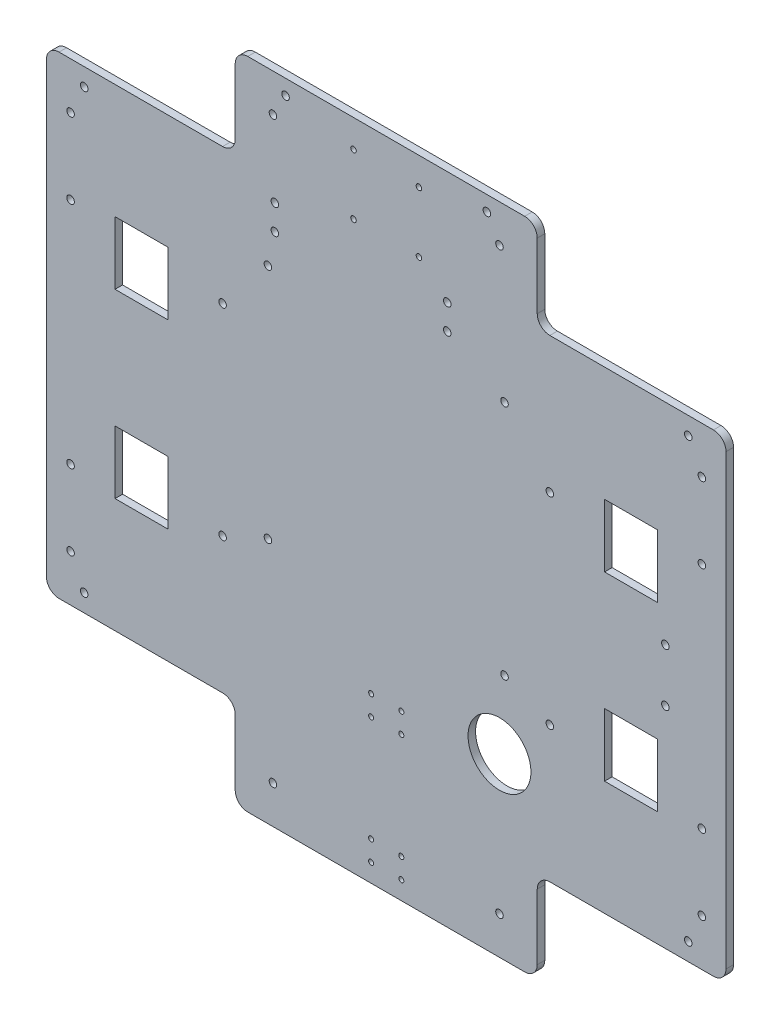
SolidWorks part; units mm, degrees
ref_plane "前视基准面" through (0, 0, 0) normal (0, 0, 1) x (1, 0, 0)
ref_plane "上视基准面" through (0, 0, 0) normal (0, 1, 0) x (1, 0, 0)
ref_plane "右视基准面" through (0, 0, 0) normal (1, 0, 0) x (0, 0, -1)
other "Configuration Table"
sketch "草图1" plane through (0, 0, 0) normal (0, 0, 1) x (1, 0, 0)
  line L1 (-135, -130) -> (135, -130)
  line L2 (-135, -130) -> (-135, 130)
  line L3 (-135, 130) -> (135, 130)
  line L4 (135, -130) -> (135, 130)
  line L5 (-135, -130) -> (135, 130) construction
  line L6 (-135, 130) -> (135, -130) construction
  point P0 (0, 0)
  dimension "D1" = 270
  dimension "D2" = 260
extrude "凸台-拉伸1" add sketch "草图1" along normal blind 3
sketch "草图2" plane through (0, 0, 0) normal (0, 0, -1) x (-1, 0, 0)
  line L0 (105.75, -40) -> (105.75, -46.5) construction
  line L1 (135, -130) -> (60, -130)
  line L2 (135, -130) -> (135, -94)
  line L3 (135, -94) -> (60, -94)
  line L4 (60, -130) -> (60, -94)
  line L5 (107.75, -48.5) -> (86.75, -48.5)
  line L6 (107.75, -48.5) -> (107.75, -23.5)
  line L7 (107.75, -23.5) -> (86.75, -23.5)
  line L8 (86.75, -48.5) -> (86.75, -23.5)
  line L9 (-135, 130) -> (-60, 130)
  line L10 (89.25, -46.5) -> (105.75, -46.5) construction
  line L11 (-179.2908, 0) -> (257.8467, 0) construction
  line L12 (0, 167.905) -> (0, -190.469) construction
  line L13 (-86.75, -48.5) -> (-86.75, -23.5)
  line L14 (-107.75, -23.5) -> (-86.75, -23.5)
  line L15 (-107.75, -48.5) -> (-107.75, -23.5)
  line L16 (-107.75, -48.5) -> (-86.75, -48.5)
  line L17 (-60, -130) -> (-60, -94)
  line L18 (-135, -94) -> (-60, -94)
  line L19 (-135, -130) -> (-135, -94)
  line L20 (-135, -130) -> (-60, -130)
  line L21 (-135, 130) -> (-135, 94)
  line L22 (-135, 94) -> (-60, 94)
  line L23 (-60, 130) -> (-60, 94)
  line L24 (-107.75, 48.5) -> (-86.75, 48.5)
  line L25 (-107.75, 48.5) -> (-107.75, 23.5)
  line L26 (-107.75, 23.5) -> (-86.75, 23.5)
  line L27 (-86.75, 48.5) -> (-86.75, 23.5)
  line L28 (86.75, 48.5) -> (86.75, 23.5)
  line L29 (107.75, 23.5) -> (86.75, 23.5)
  line L30 (107.75, 48.5) -> (107.75, 23.5)
  line L31 (107.75, 48.5) -> (86.75, 48.5)
  line L32 (60, 130) -> (60, 94)
  line L33 (135, 94) -> (60, 94)
  line L34 (135, 130) -> (135, 94)
  line L35 (135, 130) -> (60, 130)
  dimension "D1" = 36
  dimension "D2" = 75
  dimension "D3" = 25
  dimension "D4" = 21
  dimension "D5" = 2
  dimension "D6" = 2
extrude "切除-拉伸1" cut sketch "草图2" against normal up to next
fillet "圆角1" radius 5 12 edges at (135, 94, 1.5) (135, -94, 1.5) (60, -94, 1.5) (60, -130, 1.5) (-60, -130, 1.5) (-60, -94, 1.5) (-135, -94, 1.5) (-135, 94, 1.5) (-60, 94, 1.5) (-60, 130, 1.5) (60, 94, 1.5) (60, 130, 1.5)
sketch "草图3" plane through (0, 0, 3) normal (0, 0, 1) x (1, 0, 0)
  line L0 (-65.1682, -45) -> (56.9292, -45) construction
  line L1 (-50, -35) -> (50, -35) construction
  circle A0 centre (-47, -32) radius 1.5
  circle A1 centre (47, -32) radius 1.5
  circle A2 centre (47, 62) radius 1.5
  circle A3 centre (-47, 62) radius 1.5
  dimension "D1" = 10
extrude "切除-拉伸2" cut sketch "草图3" against normal blind 10
sketch "草图4" plane through (0, 0, 3) normal (0, 0, 1) x (1, 0, 0)
  line L0 (55, 130) -> (-55, 130) construction
  line L1 (60, 125) -> (60, 99) construction
  line L2 (65, 94) -> (130, 94) construction
  line L3 (135, -89) -> (135, 89) construction
  line L4 (130, -94) -> (65, -94) construction
  line L5 (135, -91) -> (135, -30) construction
  line L6 (-55, -130) -> (55, -130) construction
  line L7 (60, -99) -> (60, -125) construction
  line L8 (0, 0) -> (0, -302.2248) construction
  line L10 (-65, -40) -> (65, -40) construction
  line L11 (-65, -40) -> (-65, 40) construction
  line L12 (-65, 40) -> (65, 40) construction
  line L13 (65, -40) -> (65, 40) construction
  line L14 (-65, -40) -> (65, 40) construction
  line L15 (-65, 40) -> (65, -40) construction
  circle A1 centre (45, 115) radius 1.5
  circle A2 centre (120, 87) radius 1.5
  circle A3 centre (120, -87) radius 1.5
  circle A4 centre (45, -115) radius 1.5
  circle A5 centre (-45, -115) radius 1.5
  circle A6 centre (-120, -87) radius 1.5
  circle A7 centre (-120, 87) radius 1.5
  circle A8 centre (-45, 115) radius 1.5
  circle A11 centre (-65, 40) radius 1.5
  circle A12 centre (65, 40) radius 1.5
  circle A13 centre (-65, -40) radius 1.5
  circle A14 centre (65, -40) radius 1.5
  point P35 (0, 0)
  dimension "D1" = 15
  dimension "D2" = 15
  dimension "D3" = 3
  dimension "D4" = 7
  dimension "D5" = 15
  dimension "D6" = 3
  dimension "D7" = 7
  dimension "D8" = 15
  dimension "D9" = 3
  dimension "D10" = 15
  dimension "D11" = 15
  dimension "D12" = 3
  dimension "D15" = 3
  dimension "D16" = 3
  dimension "D17" = 3
  dimension "D18" = 3
  dimension "D13" = 130
  dimension "D14" = 80
extrude "切除-拉伸3" cut sketch "草图4" against normal through all
sketch "草图5" plane through (0, 0, 3) normal (0, 0, 1) x (1, 0, 0)
  line L0 (-149.5707, 0) -> (200.701, 0) construction
  line L1 (0, 155.8586) -> (0, -194.8252) construction
  circle A0 centre (125.4084, -45.5) radius 1.5
  circle A1 centre (125.4069, -75.5) radius 1.5
  circle A2 centre (125.4069, 75.5) radius 1.5
  circle A3 centre (125.4084, 45.5) radius 1.5
  circle A4 centre (-125.4069, -75.5) radius 1.5
  circle A5 centre (-125.4084, -45.5) radius 1.5
  circle A6 centre (-125.4084, 45.5) radius 1.5
  circle A7 centre (-125.4069, 75.5) radius 1.5
  dimension "D1" = 3
  dimension "D2" = 3
extrude "切除-拉伸4" cut sketch "草图5" against normal through all
sketch "草图6" plane through (0, 0, 3) normal (0, 0, 1) x (1, 0, 0)
  circle A0 centre (-6, -114.75) radius 1
  circle A1 centre (6, -114.75) radius 1
  circle A2 centre (-6, -122.75) radius 1
  circle A3 centre (6, -122.75) radius 1
  circle A4 centre (-6, -72.75) radius 1
  circle A5 centre (6, -72.75) radius 1
  circle A6 centre (-6, -64.75) radius 1
  circle A7 centre (6, -64.75) radius 1
extrude "切除-拉伸5" cut sketch "草图6" against normal through all
sketch "草图7" plane through (0, 0, 3) normal (0, 0, 1) x (1, 0, 0)
  circle A0 centre (110.9, 10.5) radius 1.5
  circle A1 centre (110.9, -10.5) radius 1.5
extrude "切除-拉伸6" cut sketch "草图7" against normal through all
sketch "草图8" plane through (0, 0, 3) normal (0, 0, 1) x (1, 0, 0)
  line L0 (55, 130) -> (-55, 130) construction
  line L1 (-60, 99) -> (-60, 125) construction
  line L2 (60, 125) -> (60, 99) construction
  circle A0 centre (-40, 124) radius 1.5
  circle A1 centre (40, 124) radius 1.5
  dimension "D1" = 3
  dimension "D2" = 3
  dimension "D3" = 6
  dimension "D4" = 6
  dimension "D5" = 20
  dimension "D6" = 20
extrude "切除-拉伸7" cut sketch "草图8" against normal through all
sketch "草图9" plane through (0, 0, 3) normal (0, 0, 1) x (1, 0, 0)
  circle A0 centre (-13, 119) radius 1.1
  circle A1 centre (13, 119) radius 1.1
  circle A2 centre (-13, 95) radius 1.1
  circle A3 centre (13, 95) radius 1.1
extrude "切除-拉伸8" cut sketch "草图9" against normal through all
sketch "草图10" plane through (0, 0, 3) normal (0, 0, 1) x (1, 0, 0)
  circle A0 centre (-44.25, 85.0004) radius 1.5
  circle A1 centre (-44.25, 75) radius 1.5
  circle A2 centre (24.25, 85) radius 1.5
  circle A3 centre (24.25, 75) radius 1.5
  dimension "D1" = 3
  dimension "D2" = 3
  dimension "D3" = 3
  dimension "D4" = 3
extrude "切除-拉伸9" cut sketch "草图10" against normal up to next
sketch "草图11" plane through (0, 0, 3) normal (0, 0, 1) x (1, 0, 0)
  circle A0 centre (45, -60) radius 12.5
  dimension "D1" = 25
extrude "切除-拉伸10" cut sketch "草图11" against normal blind 10
